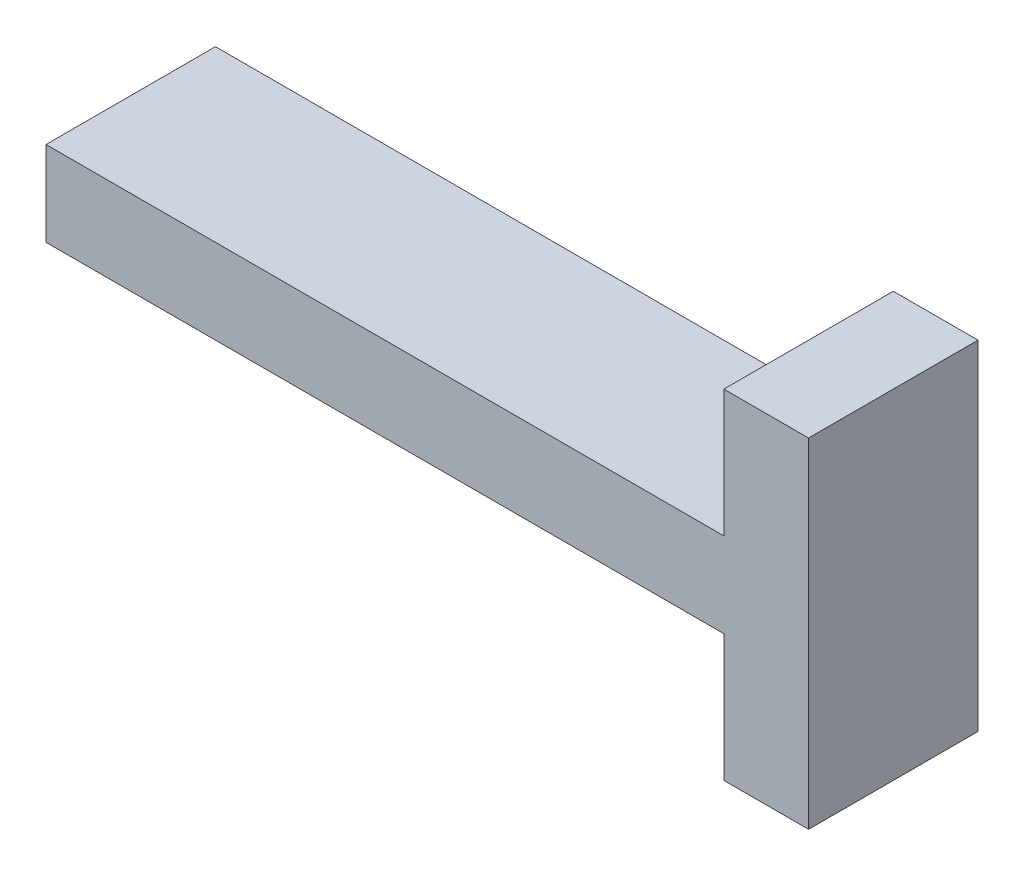
SolidWorks part; units mm, degrees
ref_plane "Front Plane" through (0, 0, 0) normal (0, 0, 1) x (1, 0, 0)
ref_plane "Top Plane" through (0, 0, 0) normal (0, 1, 0) x (1, 0, 0)
ref_plane "Right Plane" through (0, 0, 0) normal (1, 0, 0) x (0, 0, -1)
sketch "Sketch3" plane through (0, 0, 0) normal (0, 0, 1) x (1, 0, 0)
  line L0 (-61.5892, 33.2885) -> (-61.5892, -6.7115)
  line L1 (-61.5892, -6.7115) -> (-71.5892, -6.7115)
  line L2 (-71.5892, -6.7115) -> (-71.5892, 8.2885)
  line L3 (-71.5892, 8.2885) -> (-151.5892, 8.2885)
  line L4 (-151.5892, 8.2885) -> (-151.5892, 18.2885)
  line L5 (-151.5892, 18.2885) -> (-71.5892, 18.2885)
  line L6 (-71.5892, 18.2885) -> (-71.5892, 33.2885)
  line L7 (-71.5892, 33.2885) -> (-61.5892, 33.2885)
  dimension "D1" = 40
  dimension "D2" = 80
  dimension "D3" = 80
  dimension "D4" = 15
  dimension "D5" = 10
  dimension "D6" = 15
  dimension "D7" = 10
extrude "Boss-Extrude2" add sketch "Sketch3" along normal blind 20
